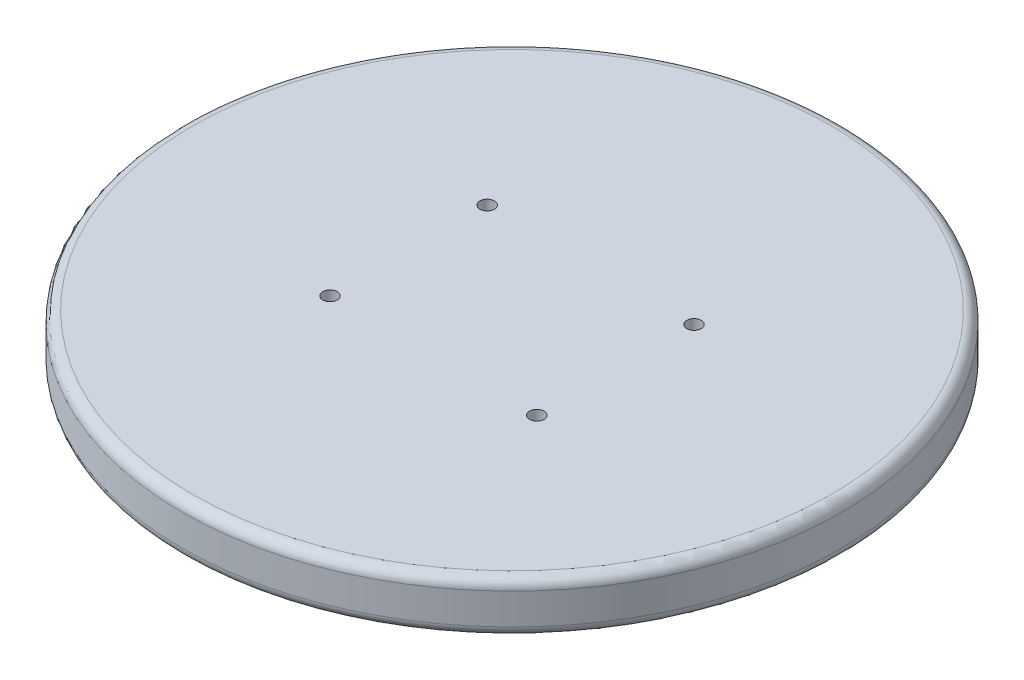
SolidWorks part; units mm, degrees
ref_plane "Front Plane" through (0, 0, 0) normal (0, 0, 1) x (1, 0, 0)
ref_plane "Top Plane" through (0, 0, 0) normal (0, 1, 0) x (1, 0, 0)
ref_plane "Right Plane" through (0, 0, 0) normal (1, 0, 0) x (0, 0, -1)
sketch "Sketch1" plane through (0, 0, 0) normal (0, 1, 0) x (1, 0, 0)
  circle A0 centre (0, 0) radius 63.7375
  circle A1 centre (20, 15.2) radius 1.4
  circle A2 centre (20, -15.2) radius 1.4
  circle A3 centre (-20, -15.2) radius 1.4
  circle A4 centre (-20, 15.2) radius 1.4
extrude "Boss-Extrude1" add sketch "Sketch1" along normal blind 10
fillet "Fillet1" radius 2 1 edges at (0, 0, 63.7375)
fillet "Fillet2" radius 2 1 edges at (0, 10, 63.7375)
